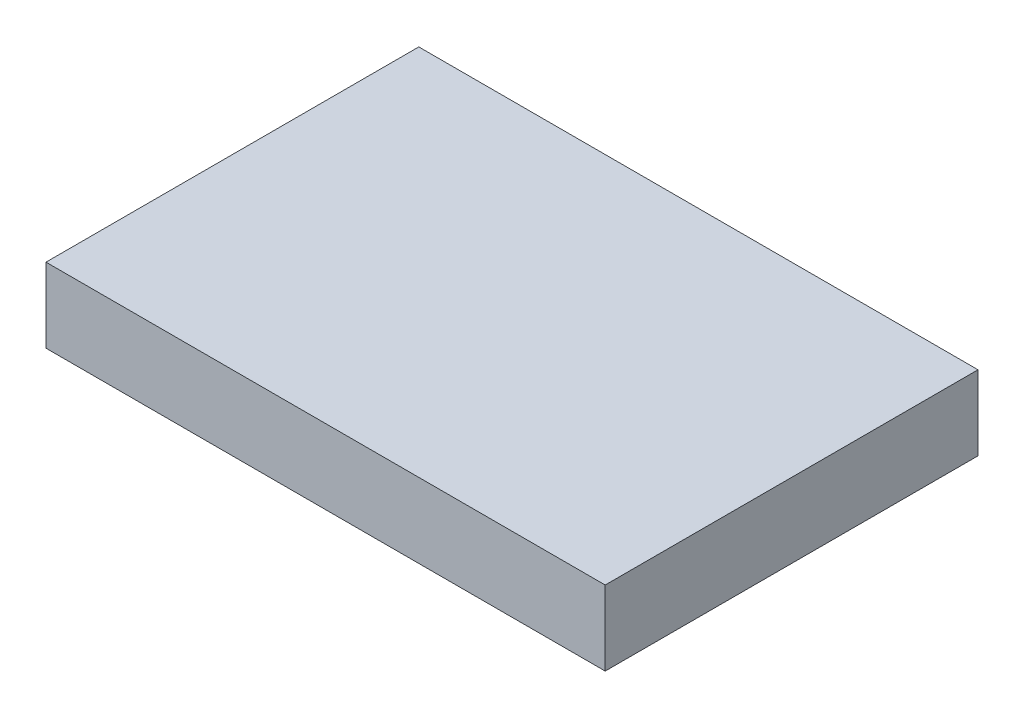
SolidWorks part; units mm, degrees
ref_plane "Front Plane" through (0, 0, 0) normal (0, 0, 1) x (1, 0, 0)
ref_plane "Top Plane" through (0, 0, 0) normal (0, 1, 0) x (1, 0, 0)
ref_plane "Right Plane" through (0, 0, 0) normal (1, 0, 0) x (0, 0, -1)
sketch "Sketch2" plane through (0, 0, 0) normal (0, 1, 0) x (1, 0, 0)
  line L1 (-37.5, 25) -> (37.5, 25)
  line L2 (-37.5, 25) -> (-37.5, -25)
  line L3 (-37.5, -25) -> (37.5, -25)
  line L4 (37.5, 25) -> (37.5, -25)
  line L5 (-37.5, 25) -> (37.5, -25) construction
  line L6 (-37.5, -25) -> (37.5, 25) construction
  point P0 (0, 0)
  dimension "D1" = 50
  dimension "D2" = 75
extrude "Plate_topview" add sketch "Sketch2" along normal blind 10
ref_plane "Midplane_topview" through (0, 5, 0) normal (0, 1, 0) x (1, 0, 0)
sketch "Sketch11" plane through (0, 5, 0) normal (0, 1, 0) x (1, 0, 0)
  line L0 (-8.5256, 0.3536) -> (-12.4305, -3.5513) construction
  line L1 (3.9279, 0.5) -> (2.478, 2.3123)
  line L2 (37.5, -25) -> (37.5, 25) construction
  line L3 (-4.6721, 0) -> (-8.1721, 0) construction
  line L4 (25, 7.5) -> (34, 7.5)
  line L5 (24.5, 7) -> (24.5, 0.5)
  line L6 (25, -7.5) -> (34, -7.5)
  line L7 (34.5, 7) -> (34.5, -7)
  line L8 (24.5, 7.5) -> (34.5, -7.5) construction
  line L9 (24.5, -7.5) -> (34.5, 7.5) construction
  line L10 (20.8279, -0.5) -> (20.8279, -14.5) construction
  line L11 (20.3279, -15) -> (18.3279, -15) construction
  line L12 (17.8279, -14.5) -> (17.8279, 14.4841) construction
  line L13 (17.3279, 14.9841) -> (15.3279, 14.9841) construction
  line L14 (14.8279, 14.4841) -> (14.8279, -14.5) construction
  line L15 (14.3279, -15) -> (12.3279, -15) construction
  line L16 (11.8279, -14.5) -> (11.8279, 14.4841) construction
  line L19 (11.3279, 14.9841) -> (9.3279, 14.9841) construction
  line L20 (8.8279, 14.4841) -> (8.8279, -14.5) construction
  line L21 (8.3279, -15) -> (6.3279, -15) construction
  line L22 (5.8279, -14.5) -> (5.8279, -0.5) construction
  line L23 (5.3279, 0) -> (4.3279, 0)
  line L24 (-19.0899, 0) -> (-4.6721, 0) construction
  line L25 (-2.4318, 2.5) -> (2.0876, 2.5)
  line L27 (-2.4318, -2.5) -> (2.0876, -2.5)
  line L29 (-2.6721, 2.5) -> (2.3279, -2.5) construction
  line L30 (-2.6721, -2.5) -> (2.3279, 2.5) construction
  line L31 (-8.1721, 0) -> (-12.2234, -4.0513) construction
  line L32 (3.9279, -0.5) -> (2.478, -2.3123)
  line L33 (-4.2721, 0.5) -> (-2.8222, 2.3123)
  line L34 (-4.2721, -0.5) -> (-2.8222, -2.3123)
  line L35 (-8.1721, 0) -> (-12.2234, 4.0513) construction
  line L36 (-12.2234, 4.0513) -> (-18.1721, 4.0513) construction
  line L37 (-24.6721, 4.5513) -> (-24.6721, 12.0513) construction
  line L38 (-18.6721, 4.5513) -> (-18.6721, 12.0513) construction
  line L39 (-18.6721, 4.0513) -> (-24.1721, 4.0513) construction
  line L40 (-18.6721, -4.5513) -> (-18.6721, -12.0513) construction
  line L41 (-24.6721, -4.5513) -> (-24.6721, -12.0513) construction
  line L42 (-18.6721, -4.0513) -> (-24.1721, -4.0513) construction
  line L43 (-12.2234, -4.0513) -> (-18.1721, -4.0513) construction
  line L44 (5.3279, -0.5) -> (3.9279, -0.5)
  line L45 (5.3279, -14.5) -> (5.3279, -0.5)
  line L46 (8.3279, -15.5) -> (6.3279, -15.5)
  line L47 (9.3279, 14.4841) -> (9.3279, -14.5)
  line L48 (11.3279, 14.4841) -> (9.3279, 14.4841)
  line L49 (11.3279, -14.5) -> (11.3279, 14.4841)
  line L50 (14.3279, -15.5) -> (12.3279, -15.5)
  line L51 (15.3279, 14.4841) -> (15.3279, -14.5)
  line L52 (17.3279, 14.4841) -> (15.3279, 14.4841)
  line L53 (17.3279, -14.5) -> (17.3279, 14.4841)
  line L54 (20.3279, -15.5) -> (18.3279, -15.5)
  line L55 (21.3279, -0.5) -> (21.3279, -14.5)
  line L56 (21.3279, -0.5) -> (24.5, -0.5)
  line L57 (-4.2721, 0.5) -> (-7.965, 0.5)
  line L58 (-8.8792, 0) -> (-12.4305, -3.5513)
  line L59 (-12.4305, -3.5513) -> (-18.1721, -3.5513)
  line L60 (-19.1721, -4.5513) -> (-19.1721, -12.0513)
  line L61 (-7.965, 0.5) -> (-12.0163, 4.5513)
  line L62 (-12.0163, 4.5513) -> (-18.1721, 4.5513)
  line L63 (-18.1721, 4.5513) -> (-18.1721, 12.0513)
  line L64 (-18.6721, 4.5513) -> (-24.1721, 4.5513)
  line L65 (-24.1721, 4.5513) -> (-24.1721, 12.0513)
  line L66 (-18.1721, -3.5513) -> (-24.1721, -3.5513)
  line L67 (-25.1721, -4.5513) -> (-25.1721, -12.0513)
  line L68 (5.3279, 0.5) -> (3.9279, 0.5)
  line L69 (6.3279, -14.5) -> (6.3279, -0.5)
  line L70 (8.3279, -14.5) -> (6.3279, -14.5)
  line L71 (8.3279, 14.4841) -> (8.3279, -14.5)
  line L72 (11.3279, 15.4841) -> (9.3279, 15.4841)
  line L73 (12.3279, -14.5) -> (12.3279, 14.4841)
  line L74 (14.3279, -14.5) -> (12.3279, -14.5)
  line L75 (14.3279, 14.4841) -> (14.3279, -14.5)
  line L76 (17.3279, 15.4841) -> (15.3279, 15.4841)
  line L77 (18.3279, -14.5) -> (18.3279, 14.4841)
  line L78 (20.3279, -14.5) -> (18.3279, -14.5)
  line L79 (20.3279, -0.5) -> (20.3279, -14.5)
  line L80 (21.3279, 0.5) -> (24.5, 0.5)
  line L81 (-4.2721, -0.5) -> (-7.965, -0.5)
  line L82 (-7.965, -0.5) -> (-12.0163, -4.5513)
  line L83 (-12.0163, -4.5513) -> (-18.1721, -4.5513)
  line L84 (-18.1721, -4.5513) -> (-18.1721, -12.0513)
  line L85 (-8.8792, 0) -> (-12.4305, 3.5513)
  line L86 (-12.4305, 3.5513) -> (-18.1721, 3.5513)
  line L87 (-19.1721, 4.5513) -> (-19.1721, 12.0513)
  line L88 (-18.1721, 3.5513) -> (-24.1721, 3.5513)
  line L89 (-25.1721, 4.5513) -> (-25.1721, 12.0513)
  line L90 (-18.6721, -4.5513) -> (-24.1721, -4.5513)
  line L91 (-24.1721, -4.5513) -> (-24.1721, -12.0513)
  line L92 (-4.6721, -0.5) -> (-8.1721, -0.5) construction
  line L93 (-4.6721, 0.5) -> (-8.1721, 0.5) construction
  line L94 (5.3279, 0.5) -> (4.3279, 0.5) construction
  line L95 (5.3279, -0.5) -> (4.3279, -0.5) construction
  line L96 (-18.6721, 3.5513) -> (-24.1721, 3.5513) construction
  line L97 (-18.6721, -3.5513) -> (-24.1721, -3.5513) construction
  line L98 (-7.8185, 0.3536) -> (-12.0163, 4.5513) construction
  line L99 (-7.8185, -0.3536) -> (-12.0163, -4.5513) construction
  line L100 (24.5, -0.5) -> (24.5, -7)
  line L101 (21.3279, 0) -> (24.5, 0) construction
  line L102 (-8.5256, -0.3536) -> (-12.4305, 3.5513) construction
  arc A0 (-24.1721, -4.0513) -> (-24.6721, -4.5513) centre (-24.1721, -4.5513) ccw construction
  arc A1 (-18.1721, -4.0513) -> (-18.6721, -4.5513) centre (-18.1721, -4.5513) ccw construction
  arc A2 (-24.1721, 4.0513) -> (-24.6721, 4.5513) centre (-24.1721, 4.5513) cw
  arc A3 (-18.6721, 4.5513) -> (-18.1721, 4.0513) centre (-18.1721, 4.5513) ccw construction
  arc A4 (9.3279, 14.9841) -> (8.8279, 14.4841) centre (9.3279, 14.4841) ccw construction
  arc A5 (11.8279, 14.4841) -> (11.3279, 14.9841) centre (11.3279, 14.4841) ccw construction
  arc A6 (15.3279, 14.9841) -> (14.8279, 14.4841) centre (15.3279, 14.4841) ccw construction
  arc A7 (17.8279, 14.4841) -> (17.3279, 14.9841) centre (17.3279, 14.4841) ccw construction
  arc A8 (-2.4318, 2.5) -> (-2.8222, 2.3123) centre (-2.4318, 2) ccw
  arc A9 (2.0876, 2.5) -> (2.478, 2.3123) centre (2.0876, 2) cw
  arc A10 (2.0876, -2.5) -> (2.478, -2.3123) centre (2.0876, -2) ccw
  arc A11 (-2.8222, -2.3123) -> (-2.4318, -2.5) centre (-2.4318, -2) ccw
  arc A12 (5.8279, -0.5) -> (5.3279, 0) centre (5.3279, -0.5) ccw
  arc A13 (6.3279, -15) -> (5.8279, -14.5) centre (6.3279, -14.5) cw construction
  arc A14 (8.8279, -14.5) -> (8.3279, -15) centre (8.3279, -14.5) cw construction
  arc A15 (12.3279, -15) -> (11.8279, -14.5) centre (12.3279, -14.5) cw construction
  arc A16 (14.8279, -14.5) -> (14.3279, -15) centre (14.3279, -14.5) cw construction
  arc A17 (18.3279, -15) -> (17.8279, -14.5) centre (18.3279, -14.5) cw construction
  arc A18 (20.8279, -14.5) -> (20.3279, -15) centre (20.3279, -14.5) cw
  arc A19 (21.3279, 0) -> (20.8279, -0.5) centre (21.3279, -0.5) ccw
  arc A20 (34, -7.5) -> (34.5, -7) centre (34, -7) ccw
  arc A21 (24.5, -7) -> (25, -7.5) centre (25, -7) ccw
  arc A22 (25, 7.5) -> (24.5, 7) centre (25, 7) ccw
  arc A23 (34, 7.5) -> (34.5, 7) centre (34, 7) cw
  arc A24 (5.3279, -0.5) -> (5.3279, -0.5) centre (5.3279, -0.5) ccw
  arc A25 (6.3279, -15.5) -> (5.3279, -14.5) centre (6.3279, -14.5) cw
  arc A26 (9.3279, -14.5) -> (8.3279, -15.5) centre (8.3279, -14.5) cw
  arc A27 (9.3279, 14.4841) -> (9.3279, 14.4841) centre (9.3279, 14.4841) ccw
  arc A28 (11.3279, 14.4841) -> (11.3279, 14.4841) centre (11.3279, 14.4841) ccw
  arc A29 (12.3279, -15.5) -> (11.3279, -14.5) centre (12.3279, -14.5) cw
  arc A30 (15.3279, -14.5) -> (14.3279, -15.5) centre (14.3279, -14.5) cw
  arc A31 (15.3279, 14.4841) -> (15.3279, 14.4841) centre (15.3279, 14.4841) ccw
  arc A32 (17.3279, 14.4841) -> (17.3279, 14.4841) centre (17.3279, 14.4841) ccw
  arc A33 (18.3279, -15.5) -> (17.3279, -14.5) centre (18.3279, -14.5) cw
  arc A34 (21.3279, -14.5) -> (20.3279, -15.5) centre (20.3279, -14.5) cw
  arc A35 (21.3279, -0.5) -> (21.3279, -0.5) centre (21.3279, -0.5) ccw
  arc A37 (-18.1721, 4.5513) -> (-18.1721, 4.5513) centre (-18.1721, 4.5513) ccw
  arc A38 (-24.1721, 4.5513) -> (-24.1721, 4.5513) centre (-24.1721, 4.5513) cw
  arc A39 (-24.1721, -3.5513) -> (-25.1721, -4.5513) centre (-24.1721, -4.5513) ccw
  arc A40 (6.3279, -0.5) -> (5.3279, 0.5) centre (5.3279, -0.5) ccw
  arc A41 (6.3279, -14.5) -> (6.3279, -14.5) centre (6.3279, -14.5) cw
  arc A42 (8.3279, -14.5) -> (8.3279, -14.5) centre (8.3279, -14.5) cw
  arc A43 (9.3279, 15.4841) -> (8.3279, 14.4841) centre (9.3279, 14.4841) ccw
  arc A44 (12.3279, 14.4841) -> (11.3279, 15.4841) centre (11.3279, 14.4841) ccw
  arc A45 (12.3279, -14.5) -> (12.3279, -14.5) centre (12.3279, -14.5) cw
  arc A46 (14.3279, -14.5) -> (14.3279, -14.5) centre (14.3279, -14.5) cw
  arc A47 (15.3279, 15.4841) -> (14.3279, 14.4841) centre (15.3279, 14.4841) ccw
  arc A48 (18.3279, 14.4841) -> (17.3279, 15.4841) centre (17.3279, 14.4841) ccw
  arc A49 (18.3279, -14.5) -> (18.3279, -14.5) centre (18.3279, -14.5) cw
  arc A50 (20.3279, -14.5) -> (20.3279, -14.5) centre (20.3279, -14.5) cw
  arc A51 (21.3279, 0.5) -> (20.3279, -0.5) centre (21.3279, -0.5) ccw
  arc A52 (-18.1721, -4.5513) -> (-18.1721, -4.5513) centre (-18.1721, -4.5513) ccw
  arc A53 (-19.1721, 4.5513) -> (-18.1721, 3.5513) centre (-18.1721, 4.5513) ccw
  arc A54 (-24.1721, 3.5513) -> (-25.1721, 4.5513) centre (-24.1721, 4.5513) cw
  arc A55 (-24.1721, -4.5513) -> (-24.1721, -4.5513) centre (-24.1721, -4.5513) ccw
  arc A56 (-18.1721, -3.5513) -> (-19.1721, -4.5513) centre (-18.1721, -4.5513) ccw construction
  point P6 (29.5, 0)
  point P14 (20.8279, 0)
  point P42 (-24.6721, -4.0513)
  point P48 (-24.6721, 4.0513)
  point P54 (8.8279, 14.9841)
  point P57 (11.8279, 14.9841)
  point P60 (14.8279, 14.9841)
  point P63 (17.8279, 14.9841)
  point P80 (5.8279, -15)
  point P83 (8.8279, -15)
  point P86 (11.8279, -15)
  point P89 (14.8279, -15)
  point P92 (17.8279, -15)
  point P95 (20.8279, -15)
  point P98 (20.8279, 0)
  point P235 (0, 0)
  dimension "D15" = 0.5
  dimension "D1" = 3
  dimension "D2" = 10
  dimension "D3" = 15
  dimension "D4" = 3
  dimension "D5" = 3
  dimension "D6" = 3
  dimension "D7" = 3
  dimension "D8" = 3
  dimension "D9" = 135
  dimension "D10" = 5
  dimension "D11" = 16.5
  dimension "D12" = 8
  dimension "D13" = 8
  dimension "D14" = 6
  dimension "D16" = 0.5
  dimension "D17" = 0.5
